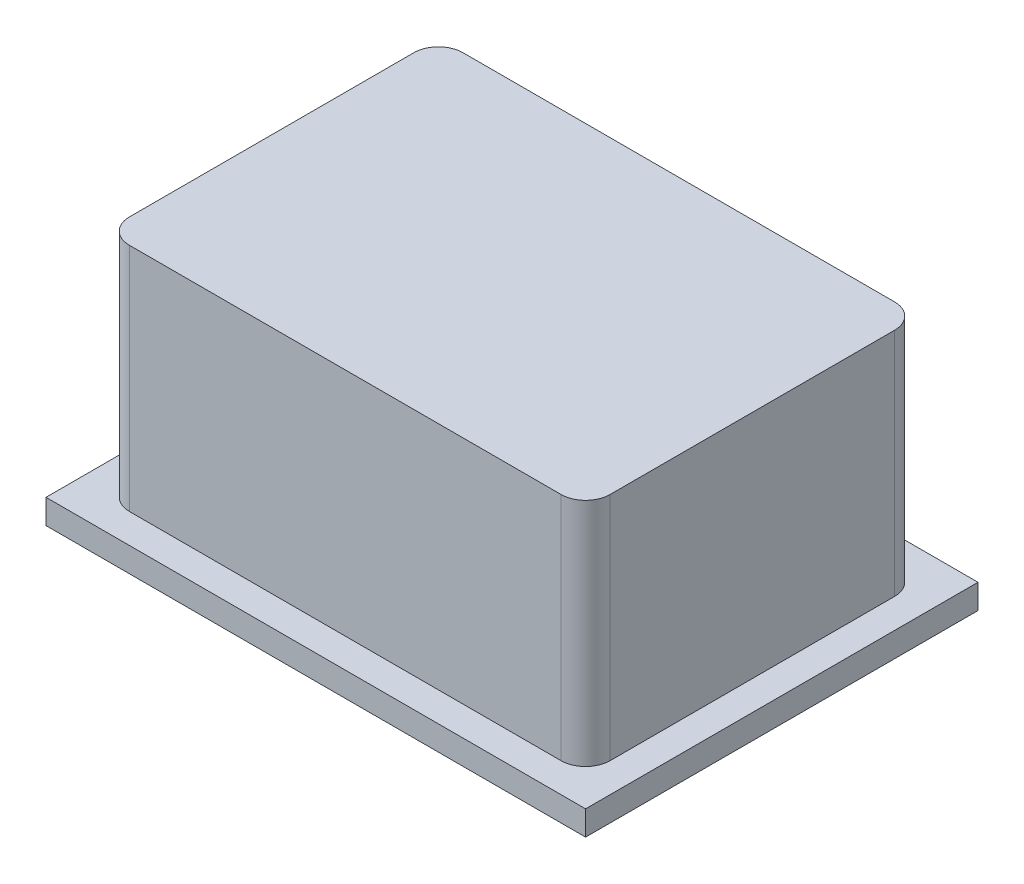
SolidWorks part; units mm, degrees
ref_plane "Front Plane" through (0, 0, 0) normal (0, 0, 1) x (1, 0, 0)
ref_plane "Top Plane" through (0, 0, 0) normal (0, 1, 0) x (1, 0, 0)
ref_plane "Right Plane" through (0, 0, 0) normal (1, 0, 0) x (0, 0, -1)
sketch "Sketch1" plane through (0, 0, 0) normal (0, 1, 0) x (1, 0, 0)
  line L1 (0, 0) -> (9.8, 0)
  line L2 (0, 0) -> (0, 6.8)
  line L3 (0, 6.8) -> (9.8, 6.8)
  line L4 (9.8, 0) -> (9.8, 6.8)
  dimension "D1" = 9.8
  dimension "D2" = 6.8
extrude "Boss-Extrude1" add sketch "Sketch1" along normal blind 4.7
sketch "Sketch2" plane through (0, 0, 0) normal (0, -1, 0) x (1, 0, 0)
  line L8 (-0.6, 0.6) -> (-0.6, -7.4)
  line L9 (-0.6, -7.4) -> (10.4, -7.4)
  line L10 (10.4, -7.4) -> (10.4, 0.6)
  line L11 (10.4, 0.6) -> (-0.6, 0.6)
  line L12 (-0.6, 0.6) -> (-0.6, -7.4)
  line L13 (-0.6, -7.4) -> (10.4, -7.4)
  line L14 (10.4, -7.4) -> (10.4, 0.6)
  line L15 (10.4, 0.6) -> (-0.6, 0.6)
  dimension "D1" = 0.6
extrude "Boss-Extrude2" add sketch "Sketch2" along normal blind 0.5
sketch "Sketch3" plane through (0, -0.5, 0) normal (0, -1, 0) x (1, 0, 0)
  line L8 (8.9, -0.9) -> (0.9, -0.9)
  line L9 (0.9, -0.9) -> (0.9, -5.9)
  line L10 (0.9, -5.9) -> (8.9, -5.9)
  line L11 (8.9, -5.9) -> (8.9, -0.9)
  line L12 (8.9, -0.9) -> (0.9, -0.9)
  line L13 (0.9, -0.9) -> (0.9, -5.9)
  line L14 (0.9, -5.9) -> (8.9, -5.9)
  line L15 (8.9, -5.9) -> (8.9, -0.9)
  dimension "D1" = 1.5
extrude "Cut-Extrude1" cut sketch "Sketch3" against normal blind 3.7
fillet "Fillet1" radius 0.5 4 edges at (9.8, 2.35, -6.8) (0, 2.35, -6.8) (9.8, 2.35, 0) (0, 2.35, 0)
